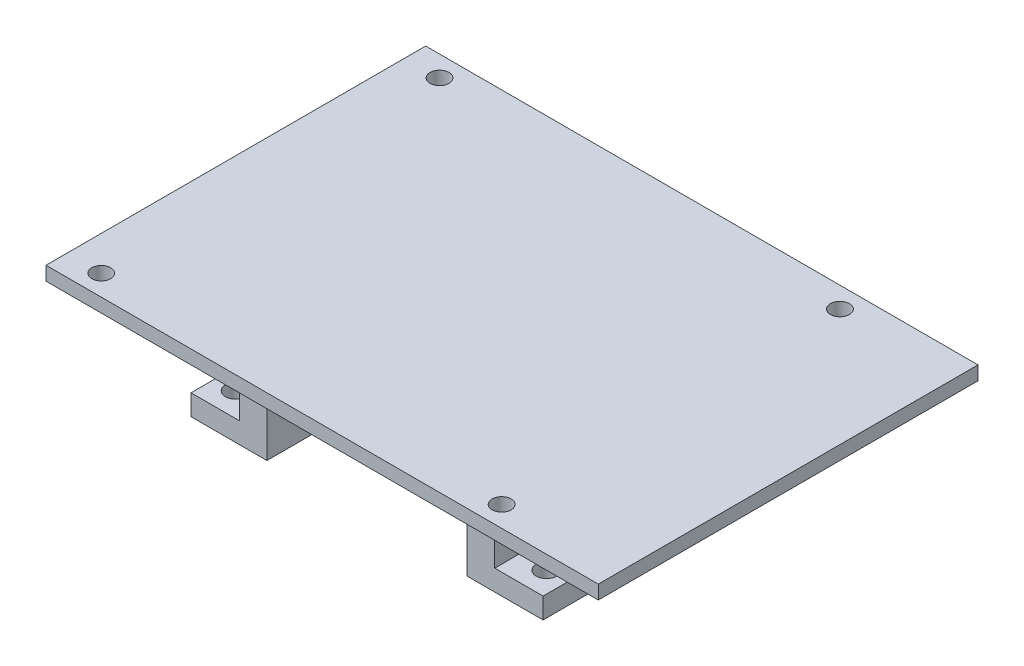
SolidWorks part; units mm, degrees
ref_plane "前基準面" through (0, 0, 0) normal (0, 0, 1) x (1, 0, 0)
ref_plane "上基準面" through (0, 0, 0) normal (0, 1, 0) x (1, 0, 0)
ref_plane "右基準面" through (0, 0, 0) normal (1, 0, 0) x (0, 0, -1)
sketch "草圖1" plane through (0, 0, 0) normal (0, 0, 1) x (1, 0, 0)
  line L0 (-133.4262, 0) -> (6537.8852, 0) construction
  line L1 (0, -133.4262) -> (0, 6537.8852) construction
  line L2 (-25.5, 0) -> (-25.5, 3)
  line L3 (-25.5, 3) -> (-18.5, 3)
  line L4 (-18.5, 3) -> (-18.5, 13)
  line L6 (18.5, 13) -> (18.5, 3)
  line L7 (18.5, 3) -> (25.5, 3)
  line L8 (25.5, 3) -> (25.5, 0)
  line L10 (-14.5, 0) -> (-14.5, 13)
  line L11 (-14.5, 13) -> (14.5, 13)
  line L12 (14.5, 13) -> (14.5, 0)
  line L13 (-25.5, 0) -> (-14.5, 0)
  line L14 (14.5, 0) -> (25.5, 0)
  line L16 (-40, 15) -> (-40, 13)
  line L17 (-18.5, 13) -> (-40, 13)
  line L18 (-40, 15) -> (40, 15)
  line L19 (40, 15) -> (40, 13)
  line L20 (40, 13) -> (18.5, 13)
  dimension "D1" = 4
  dimension "D2" = 15
  dimension "D3" = 7
  dimension "D4" = 51
  dimension "D5" = 2
  dimension "D6" = 3
  dimension "D7" = 80
extrude "填料-伸長1" add sketch "草圖1" along normal mid plane 55
ref_plane "平面1" through (0, 0, 0) normal (0, -1, 0) x (-1, 0, 0)
sketch "草圖4" plane through (0, 0, 0) normal (0, -1, 0) x (-1, 0, 0)
  line L0 (-1000, 0) -> (49000, 0) construction
  line L1 (-22.5, -983.7325) -> (-22.5, 49016.2675) construction
  line L2 (22.5, -979.835) -> (22.5, 49020.165) construction
  line L3 (0, -1000) -> (0, 49000) construction
  line L4 (-1025.2209, 17.5) -> (48974.7791, 17.5) construction
  line L5 (-1026.821, -17.5) -> (48973.179, -17.5) construction
  circle A0 centre (-22.5, 17.5) radius 1.5
  circle A1 centre (-22.5, -17.5) radius 1.5
  circle A2 centre (22.5, -17.5) radius 1.5
  circle A3 centre (22.5, 17.5) radius 1.5
  dimension "D1" = 3
  dimension "D2" = 35
  dimension "D3" = 45
extrude "除料-伸長1" cut sketch "草圖4" against normal up to next
sketch "草圖5" plane through (0, 0, 0) normal (0, -1, 0) x (-1, 0, 0)
  line L0 (25.5, -27.5) -> (25.5, 27.5) construction
  line L1 (-25.5, 27.5) -> (25.5, 27.5)
  line L2 (-25.5, 27.5) -> (-25.5, 21)
  line L3 (-25.5, 21) -> (25.5, 21)
  line L4 (25.5, 27.5) -> (25.5, 21)
  line L5 (-25.5, -27.5) -> (-25.5, 27.5) construction
  line L6 (-25.5, 14) -> (25.5, 14)
  line L7 (-25.5, 14) -> (-25.5, -14)
  line L8 (-25.5, -14) -> (25.5, -14)
  line L9 (25.5, 14) -> (25.5, -14)
  line L10 (-1022.5, 17.5) -> (48977.5, 17.5) construction
  line L11 (-25.5, -27.5) -> (25.5, -27.5)
  line L12 (-25.5, -27.5) -> (-25.5, -21)
  line L13 (-25.5, -21) -> (25.5, -21)
  line L14 (25.5, -27.5) -> (25.5, -21)
  line L15 (-1022.5, -17.5) -> (48977.5, -17.5) construction
  dimension "D1" = 7
  dimension "D2" = 7
extrude "除料-伸長2" cut sketch "草圖5" against normal up to surface (13 mm away) up to face at (0, 13, 0)
sketch "草圖6" plane through (0, 15, 0) normal (0, 1, 0) x (1, 0, 0)
  line L0 (-1000, 0) -> (49000, 0) construction
  line L1 (-35, -975.4137) -> (-35, 49024.5863) construction
  line L2 (23, -978.5726) -> (23, 49021.4274) construction
  line L3 (-1042.6676, 24.5) -> (48957.3324, 24.5) construction
  line L4 (-1038.3461, -24.5) -> (48961.6539, -24.5) construction
  line L5 (-40, -27.5) -> (-40, 27.5) construction
  circle A0 centre (-35, 24.5) radius 1.375
  circle A1 centre (-35, -24.5) radius 1.375
  circle A2 centre (23, -24.5) radius 1.375
  circle A3 centre (23, 24.5) radius 1.375
  dimension "D1" = 2.75
  dimension "D2" = 49
  dimension "D3" = 58
  dimension "D4" = 5
extrude "除料-伸長3" cut sketch "草圖6" against normal up to next
